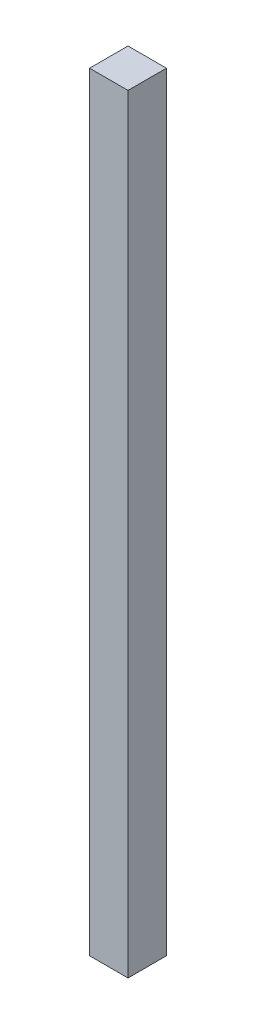
SolidWorks part; units mm, degrees
ref_plane "Front Plane" through (0, 0, 0) normal (0, 0, 1) x (1, 0, 0)
ref_plane "Top Plane" through (0, 0, 0) normal (0, 1, 0) x (1, 0, 0)
ref_plane "Right Plane" through (0, 0, 0) normal (1, 0, 0) x (0, 0, -1)
sketch "Sketch1" plane through (0, 0, 0) normal (0, 1, 0) x (1, 0, 0)
  line L1 (-10, 10) -> (10, 10)
  line L2 (-10, 10) -> (-10, -10)
  line L3 (-10, -10) -> (10, -10)
  line L4 (10, 10) -> (10, -10)
  line L5 (-10, 10) -> (10, -10) construction
  line L6 (-10, -10) -> (10, 10) construction
  point P0 (0, 0)
  dimension "D1" = 20
  dimension "D2" = 20
extrude "Boss-Extrude1" add sketch "Sketch1" along normal blind 400
